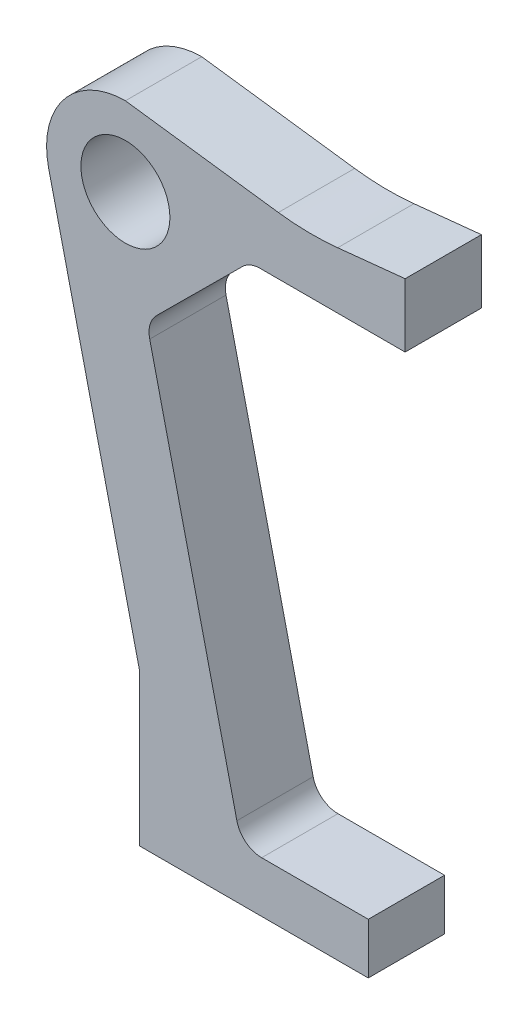
SolidWorks part; units mm, degrees
ref_plane "Plan de face" through (0, 0, 0) normal (0, 0, 1) x (1, 0, 0)
ref_plane "Plan de dessus" through (0, 0, 0) normal (0, 1, 0) x (1, 0, 0)
ref_plane "Plan de droite" through (0, 0, 0) normal (1, 0, 0) x (0, 0, -1)
sketch "Esquisse1" plane through (0, 0, 0) normal (0, 0, 1) x (1, 0, 0)
  line L0 (0.9811, 13.3706) -> (4.55, -1.925)
  line L1 (4.55, -7.925) -> (13.55, -7.925)
  line L2 (13.55, -7.925) -> (13.55, -5.925)
  line L3 (13.55, -5.925) -> (9.3574, -5.925)
  line L4 (8.3836, -5.1522) -> (4.9562, 9.5368)
  line L6 (15, 16.6156) -> (15, 14.1156)
  line L8 (4.55, -1.925) -> (4.55, -7.925)
  line L9 (11.55, 10.2) -> (11.55, -10.2) construction
  line L10 (5.225, 10.4732) -> (8.596, 13.8248)
  line L11 (10, -12.5) -> (10, 17.5) construction
  line L12 (15, 14.1156) -> (9.3011, 14.1156)
  line L13 (11.3195, 16.7099) -> (16.2935, 17.2196) construction
  line L14 (11.3195, 16.7099) -> (16.2935, 17.2196) construction
  line L15 (4, 17.175) -> (10.015, 16.3783)
  line L16 (15, 16.6156) -> (12.3474, 16.3438)
  arc A3 (4, 17.175) -> (0.9811, 13.3706) centre (4, 14.075) ccw
  arc A4 (9.3574, -5.925) -> (8.3836, -5.1522) centre (9.3574, -4.925) cw
  arc A6 (9.3011, 14.1156) -> (8.596, 13.8248) centre (9.3011, 13.1156) ccw
  arc A7 (4.9562, 9.5368) -> (5.225, 10.4732) centre (5.93, 9.7641) cw
  circle A8 centre (4, 14.075) radius 1.75
  arc A9 (12.3474, 16.3438) -> (10.015, 16.3783) centre (11.3281, 26.2917) cw
  point P17 (4, 10.975)
  point P27 (0, 0)
  point P29 (0, 0)
  dimension "D2" = 6.2
  dimension "D5" = 6
  dimension "D6" = 1
  dimension "D14" = 0.5
  dimension "D4" = 1
  dimension "D13" = 3.5
  dimension "D15" = 10
  dimension "D3" = 2.5
  dimension "D7" = 2
  dimension "D8" = 2
  dimension "D9" = 9
  dimension "D10" = 5
  dimension "D11" = 19
  dimension "D12" = 3
extrude "Boss.-Extru.1" add sketch "Esquisse1" along normal blind 3 from offset 0.2
